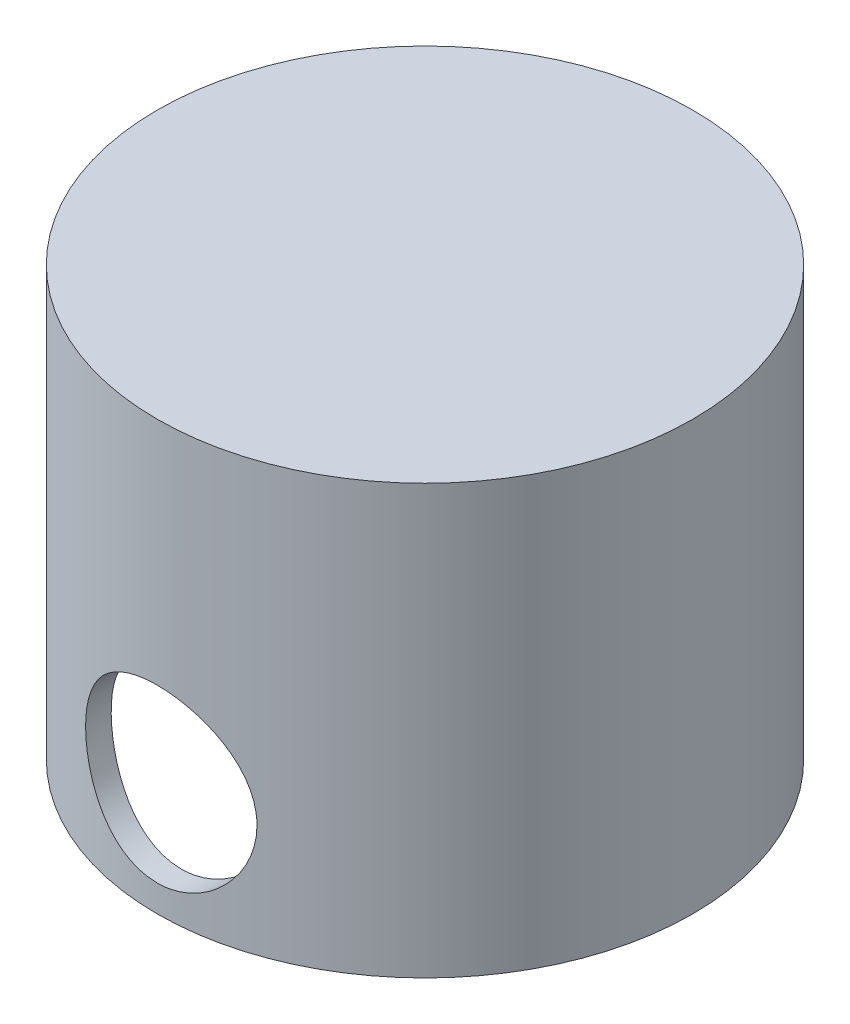
SolidWorks part; units mm, degrees
ref_plane "Front Plane" through (0, 0, 0) normal (0, 0, 1) x (1, 0, 0)
ref_plane "Top Plane" through (0, 0, 0) normal (0, 1, 0) x (1, 0, 0)
ref_plane "Right Plane" through (0, 0, 0) normal (1, 0, 0) x (0, 0, -1)
sketch "Sketch2" plane through (0, 0, 0) normal (0, 1, 0) x (1, 0, 0)
  circle A0 centre (0, 0) radius 5
  dimension "D1" = 10
sketch "Sketch4" plane through (0, 0, 0) normal (0, 1, 0) x (1, 0, 0)
  circle A0 centre (0, 0) radius 4.55
  dimension "D1" = 9.1
extrude "Boss-Extrude1" add sketch "Sketch2" along normal blind 8 contours A0
extrude "Cut-Extrude1" cut sketch "Sketch4" along normal blind 7.1
sketch "Sketch11" plane through (0, 0, 0) normal (0, 0, 1) x (1, 0, 0)
  line L0 (-5, 0) -> (-5, 7.1)
  line L1 (-5, 8) -> (-5, 0) construction
  line L2 (-5, 7.1) -> (-5, 2.1)
  line L3 (-5, 2.1) -> (-1.6, 2.1)
  line L4 (5, 2.1) -> (4.9985, 2.1012)
  line L5 (1.6, 2.1) -> (5, 2.1)
  circle A0 centre (0, 2.1) radius 1.6
  dimension "D4" = 3.2
  dimension "D1" = 7.1
  dimension "D2" = 5
  dimension "D3" = 10
extrude "Cut-Extrude2" cut sketch "Sketch11" against normal through all both and the other way through all contours A0
